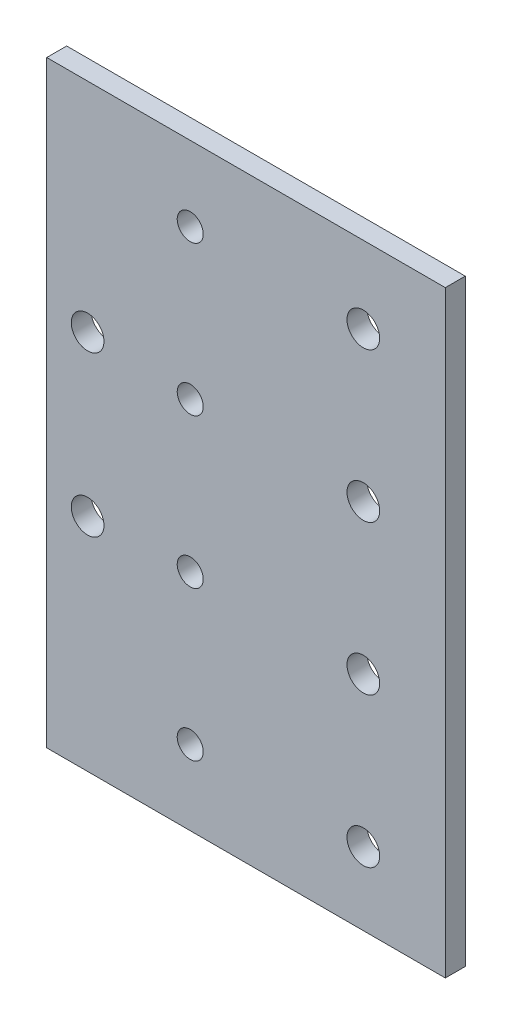
SolidWorks part; units mm, degrees
ref_plane "Front Plane" through (0, 0, 0) normal (0, 0, 1) x (1, 0, 0)
ref_plane "Top Plane" through (0, 0, 0) normal (0, 1, 0) x (1, 0, 0)
ref_plane "Right Plane" through (0, 0, 0) normal (1, 0, 0) x (0, 0, -1)
sketch "Sketch2" plane through (0, 0, 0) normal (0, 0, 1) x (1, 0, 0)
  line L0 (-123.0109, -74.4947) -> (-143.5848, -74.4947) construction
  line L1 (-123.0109, 0.5053) -> (-223.0109, 0.5053)
  line L2 (-123.0109, 0.5053) -> (-123.0109, -149.4947)
  line L3 (-123.0109, -149.4947) -> (-223.0109, -149.4947)
  line L4 (-223.0109, 0.5053) -> (-223.0109, -149.4947)
  line L5 (-143.5848, -74.4947) -> (-143.5848, -56.25) construction
  line L7 (-212.756, -54.0129) -> (-223.0109, -54.0129) construction
  line L8 (-212.756, -94.0129) -> (-223.0109, -94.0129) construction
  line L10 (-143.5848, -56.25) -> (-143.5848, -18.75) construction
  line L11 (-143.5848, -74.4947) -> (-143.5848, -93.75) construction
  line L12 (-143.5848, -93.75) -> (-143.5848, -131.25) construction
  circle A3 centre (-212.756, -54.0129) radius 4.165
  circle A4 centre (-212.756, -94.0129) radius 4.165
  circle A5 centre (-143.5848, -18.75) radius 3.15
  circle A6 centre (-143.5848, -56.25) radius 3.15
  circle A7 centre (-143.5848, -93.75) radius 3.15
  circle A8 centre (-143.5848, -131.25) radius 3.15
  dimension "D1" = 100
  dimension "D2" = 150
extrude "Boss-Extrude1" add sketch "Sketch2" along normal blind 5 contours L4 L3 L2 L1
sketch "Sketch3" plane through (0, 0, 0) normal (0, 0, -1) x (-1, 0, 0)
  circle A3 centre (212.756, -54.0129) radius 4.1021
  circle A4 centre (212.756, -94.0129) radius 4.1021
  circle A5 centre (143.5848, -18.75) radius 4.1021
  circle A6 centre (143.5848, -56.25) radius 4.1021
  circle A7 centre (143.5848, -93.75) radius 4.1021
  circle A8 centre (143.5848, -131.25) radius 4.1021
  dimension "D1" = 8.2042
extrude "Cut-Extrude1" cut sketch "Sketch3" against normal blind 5
sketch "Sketch6" plane through (0, 0, 5) normal (0, 0, 1) x (1, 0, 0)
  line L0 (-223.0109, 0.5053) -> (-187.0109, 0.5053) construction
  line L1 (-187.0109, 0.5053) -> (-187.0109, -149.4947) construction
  line L3 (-187.0109, -149.4947) -> (-187.0109, -74.4947) construction
  line L4 (-187.0109, -74.4947) -> (-187.0109, -111.9947) construction
  line L5 (-187.0109, -111.9947) -> (-187.0109, -93.2447) construction
  line L6 (-187.0109, -111.9947) -> (-187.0109, -149.4947) construction
  line L7 (-187.0109, -149.4947) -> (-187.0109, -130.7447) construction
  line L8 (-187.0109, -74.4947) -> (-187.0109, 0.5053) construction
  line L9 (-187.0109, 0.5053) -> (-187.0109, -36.9947) construction
  line L10 (-187.0109, -36.9947) -> (-187.0109, -18.2447) construction
  line L11 (-187.0109, -36.9947) -> (-187.0109, -74.4947) construction
  line L12 (-187.0109, -74.4947) -> (-187.0109, -55.7447) construction
  line L13 (-223.0109, -149.4947) -> (-187.0109, -149.4947) construction
  circle A0 centre (-187.0109, -18.2447) radius 3.2639
  circle A1 centre (-187.0109, -55.7447) radius 3.2639
  circle A2 centre (-187.0109, -93.2447) radius 3.2639
  circle A3 centre (-187.0109, -130.7447) radius 3.2639
  dimension "D1" = 6.5278
  dimension "D2" = 36
extrude "Cut-Extrude2" cut sketch "Sketch6" against normal through all
